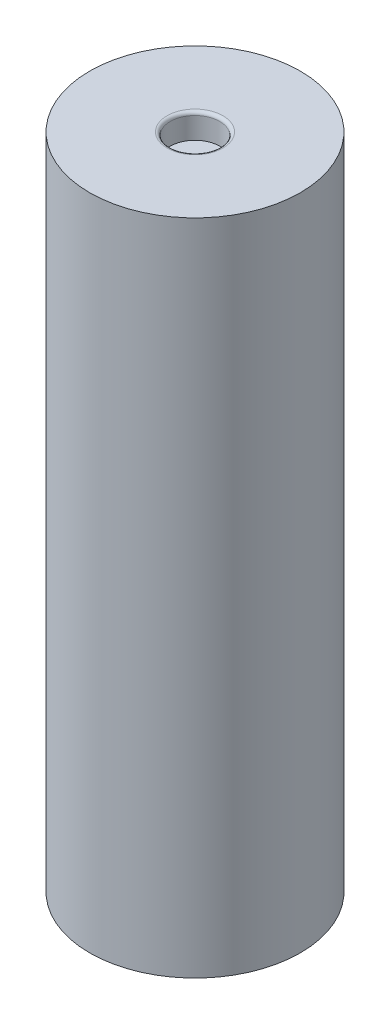
SolidWorks part; units mm, degrees
ref_plane "Front Plane" through (0, 0, 0) normal (0, 0, 1) x (1, 0, 0)
ref_plane "Top Plane" through (0, 0, 0) normal (0, 1, 0) x (1, 0, 0)
ref_plane "Right Plane" through (0, 0, 0) normal (1, 0, 0) x (0, 0, -1)
sketch "Sketch1" plane through (0, 0, 0) normal (0, 1, 0) x (1, 0, 0)
  circle A0 centre (0, 0) radius 6.4
  dimension "D1" = 12.8
extrude "Boss-Extrude1" add sketch "Sketch1" along normal blind 40
sketch "Sketch2" plane through (0, 40, 0) normal (0, 1, 0) x (1, 0, 0)
  circle A0 centre (0, 0) radius 1.5
  dimension "D1" = 3
extrude "Cut-Extrude1" cut sketch "Sketch2" against normal blind 1.5
ref_plane "Plane1" through (0, 20, 0) normal (0, 1, 0) x (1, 0, 0)
mirror "Mirror1" about plane through (0, 20, 0) normal (0, 1, 0) of "Cut-Extrude1"
fillet "Fillet2" radius 0.2 2 edges at (0, 0, 1.5) (0, 40, 1.5)
